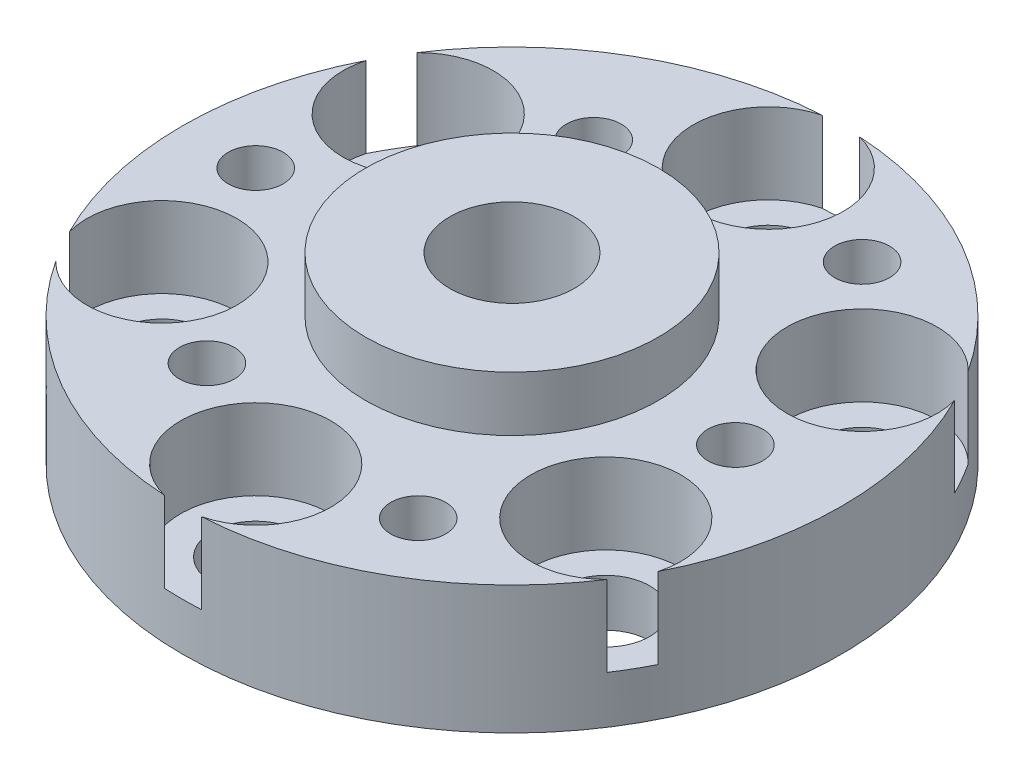
SolidWorks part; units mm, degrees
material "6061-T6 (SS)"
ref_plane "Front Plane" through (0, 0, 0) normal (0, 0, 1) x (1, 0, 0)
ref_plane "Top Plane" through (0, 0, 0) normal (0, 1, 0) x (1, 0, 0)
ref_plane "Right Plane" through (0, 0, 0) normal (1, 0, 0) x (0, 0, -1)
sketch "Sketch1" plane through (0, 0, 0) normal (0, 1, 0) x (1, 0, 0)
  circle A0 centre (0, 0) radius 18
  dimension "D1" = 36
extrude "Boss-Extrude1" add sketch "Sketch1" along normal blind 7
sketch "Sketch2" plane through (0, 7, 0) normal (0, 1, 0) x (1, 0, 0)
  circle A0 centre (0, 0) radius 14
  point P4 (0, 14)
  point P11 (12.1244, 7)
  point P12 (12.1244, -7)
  point P13 (0, -14)
  point P14 (-12.1244, -7)
  point P15 (-12.1244, 7)
  dimension "D1" = 28
  dimension "D2" = 6
hole_wizard "CBORE for M4 Hex Socket Head Cap Screw2" positions "Sketch2" profile "Sketch3" counterbore size "M4" standard "DIN"
sketch "Sketch3" plane through (-12.1244, 7, -7) normal (1, 0, 0) x (0, 0, 1)
  line L0 (0, 0) -> (0, 11.4421)
  line L1 (0, 11.4421) -> (2.4, 10)
  line L2 (2.4, 10) -> (2.4, 4.4)
  line L3 (2.4, 4.4) -> (4.1, 4.4)
  line L4 (4.1, 4.4) -> (4.1, 0)
  line L5 (4.1, 0) -> (0, 0)
  line L10 (0, 11.4421) -> (-2.4, 10) construction
  line L11 (0, -6.35) -> (0, 107.95) construction
  dimension "Hole Dia." = 4.8
  dimension "Hole Depth" = 10
  dimension "C'Bore Dia." = 8.2
  dimension "C'Bore Depth" = 4.4
  dimension "Drill Angle" = 118
sketch "Sketch4" plane through (0, 7, 0) normal (0, 1, 0) x (1, 0, 0)
  circle A0 centre (0, 0) radius 14
  point P5 (-14, 0)
  point P10 (7, 12.1244)
  point P11 (7, -12.1244)
  dimension "D1" = 28
  dimension "D2" = 3
hole_wizard "Ø3.0mm Dowel Hole1" positions "Sketch4" profile "Sketch5" hole size "Ø3.0" standard "DIN"
sketch "Sketch5" plane through (7, 7, 12.1244) normal (1, 0, 0) x (0, 0, 1)
  line L0 (0, 0) -> (0, 10.9013)
  line L1 (0, 10.9013) -> (1.5, 10)
  line L2 (1.5, 10) -> (1.5, 0)
  line L5 (1.5, 0) -> (0, 0)
  line L10 (0, 10.9013) -> (-1.5, 10) construction
  line L11 (0, -6.35) -> (0, 107.95) construction
  dimension "Hole Dia." = 3
  dimension "Hole Depth" = 10
  dimension "Drill Angle" = 118
sketch "Sketch6" plane through (0, 7, 0) normal (0, 1, 0) x (1, 0, 0)
  circle A1 centre (0, 0) radius 12.2
  point P7 (12.2, 0)
  point P13 (-6.1, -10.5655)
  point P14 (-6.1, 10.5655)
  dimension "D1" = 24.4
  dimension "D2" = 3
hole_wizard "Ø3.0mm Dowel Hole2" positions "Sketch6" profile "Sketch7" hole size "Ø3.0" standard "DIN"
sketch "Sketch7" plane through (-6.1, 7, -10.5655) normal (1, 0, 0) x (0, 0, 1)
  line L0 (0, 0) -> (0, 10.9013)
  line L1 (0, 10.9013) -> (1.5, 10)
  line L2 (1.5, 10) -> (1.5, 0)
  line L5 (1.5, 0) -> (0, 0)
  line L10 (0, 10.9013) -> (-1.5, 10) construction
  line L11 (0, -6.35) -> (0, 107.95) construction
  dimension "Hole Dia." = 3
  dimension "Hole Depth" = 10
  dimension "Drill Angle" = 118
sketch "Sketch8" plane through (0, 7, 0) normal (0, 1, 0) x (1, 0, 0)
  circle A0 centre (0, 0) radius 8
  dimension "D1" = 16
extrude "Boss-Extrude2" add sketch "Sketch8" along normal blind 3
sketch "Sketch9" plane through (0, 10, 0) normal (0, 1, 0) x (1, 0, 0)
  point P0 (0, 0)
hole_wizard "Tap Drill for M8 Tap1" positions "Sketch9" profile "Sketch11" hole size "M8" standard "DIN" end condition through all
sketch "Sketch11" plane through (0, 10, 0) normal (1, 0, 0) x (0, 0, 1)
  line L0 (0, 0) -> (0, 10)
  line L1 (0, 10) -> (3.4, 10)
  line L2 (3.4, 10) -> (3.4, 0)
  line L5 (3.4, 0) -> (0, 0)
  line L11 (0, -6.35) -> (0, 107.95) construction
  dimension "Thru Hole Dia." = 6.8
  dimension "Thru Hole Depth" = 10
